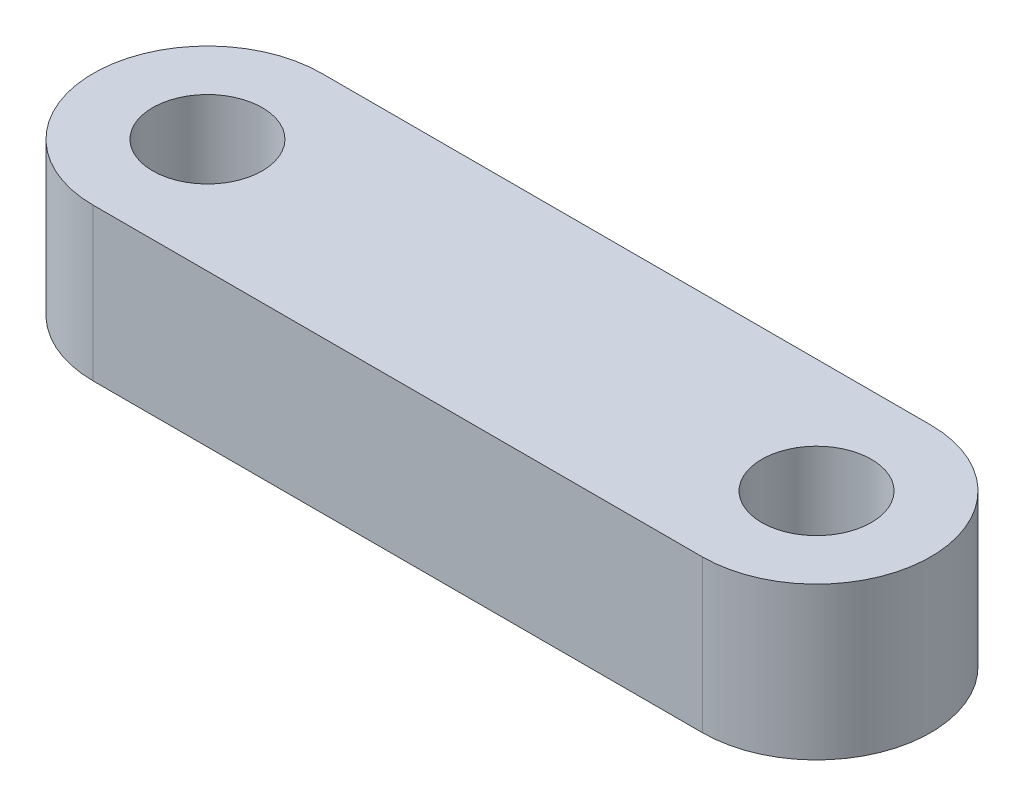
SolidWorks part; units mm, degrees
ref_plane "Front Plane" through (0, 0, 0) normal (0, 0, 1) x (1, 0, 0)
ref_plane "Top Plane" through (0, 0, 0) normal (0, 1, 0) x (1, 0, 0)
ref_plane "Right Plane" through (0, 0, 0) normal (1, 0, 0) x (0, 0, -1)
sketch "Sketch1" plane through (0, 0, 0) normal (0, 1, 0) x (1, 0, 0)
  line L0 (0, 0) -> (-25.4, 0) construction
  line L1 (0, -4.7625) -> (-25.4, -4.7625)
  line L2 (0, 4.7625) -> (-25.4, 4.7625)
  arc A0 (0, -4.7625) -> (0, 4.7625) centre (0, 0) ccw
  arc A1 (-25.4, 4.7625) -> (-25.4, -4.7625) centre (-25.4, 0) ccw
  circle A2 centre (-25.4, 0) radius 2.286
  circle A3 centre (0, 0) radius 2.286
  point P3 (-12.7, 0)
  dimension "D2" = 4.7625
  dimension "D3" = 4.572
  dimension "D1" = 25.4
extrude "Boss-Extrude1" add sketch "Sketch1" along normal blind 6.35
